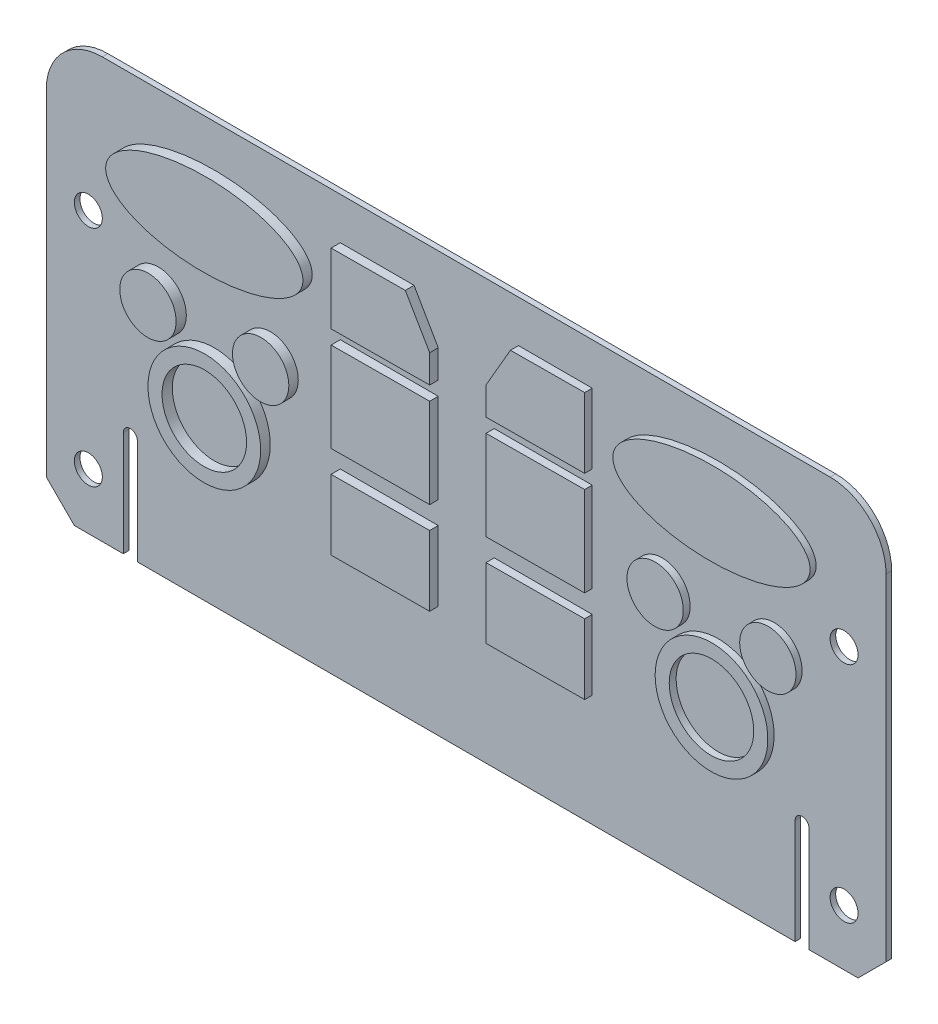
SolidWorks part; units mm, degrees
ref_plane "Front Plane" through (0, 0, 0) normal (0, 0, 1) x (1, 0, 0)
ref_plane "Top Plane" through (0, 0, 0) normal (0, 1, 0) x (1, 0, 0)
ref_plane "Right Plane" through (0, 0, 0) normal (1, 0, 0) x (0, 0, -1)
sketch "Sketch1" plane through (0, 0, 0) normal (0, 0, 1) x (1, 0, 0)
  line L1 (-300, 150) -> (0, 150)
  line L2 (-300, 150) -> (-300, 0)
  line L3 (-300, 0) -> (0, 0)
  line L4 (0, 150) -> (0, 0)
  line L5 (-300, 150) -> (0, 0) construction
  line L6 (-300, 0) -> (0, 150) construction
  point P0 (-150, 75)
  dimension "D1" = 300
  dimension "D2" = 150
extrude "PCB Base" add sketch "Sketch1" along normal blind 2
sketch "Sketch4" plane through (0, 0, 0) normal (0, 0, -1) x (-1, 0, 0)
  line L0 (140, 120) -> (131.3397, 135)
  line L1 (105, 40) -> (140, 40)
  line L2 (105, 40) -> (105, 65)
  line L3 (105, 65) -> (140, 65)
  line L4 (140, 40) -> (140, 65)
  line L5 (105, 40) -> (140, 65) construction
  line L6 (105, 65) -> (140, 40) construction
  line L7 (105, 73) -> (140, 73)
  line L8 (105, 73) -> (105, 105)
  line L9 (105, 105) -> (140, 105)
  line L10 (140, 73) -> (140, 105)
  line L11 (105, 73) -> (140, 105) construction
  line L12 (105, 105) -> (140, 73) construction
  line L13 (105, 110) -> (140, 110)
  line L14 (105, 110) -> (105, 135)
  line L15 (105, 135) -> (131.3397, 135)
  line L16 (140, 110) -> (140, 120)
  line L17 (105, 110) -> (133.8684, 130.6203) construction
  line L18 (105, 135) -> (140, 110) construction
  line L19 (150, 0) -> (150, 150) construction
  line L20 (300, 0) -> (0, 0) construction
  line L21 (0, 150) -> (300, 150) construction
  line L22 (195, 135) -> (160, 110) construction
  line L23 (195, 110) -> (166.1316, 130.6203) construction
  line L24 (195, 105) -> (160, 73) construction
  line L25 (195, 73) -> (160, 105) construction
  line L26 (195, 65) -> (160, 40) construction
  line L27 (195, 40) -> (160, 65) construction
  line L28 (160, 110) -> (160, 120)
  line L29 (195, 135) -> (168.6603, 135)
  line L30 (195, 110) -> (195, 135)
  line L31 (195, 110) -> (160, 110)
  line L32 (160, 73) -> (160, 105)
  line L33 (195, 105) -> (160, 105)
  line L34 (195, 73) -> (195, 105)
  line L35 (195, 73) -> (160, 73)
  line L36 (160, 40) -> (160, 65)
  line L37 (195, 65) -> (160, 65)
  line L38 (195, 40) -> (195, 65)
  line L39 (195, 40) -> (160, 40)
  line L40 (160, 120) -> (168.6603, 135)
  circle A0 centre (40, 85) radius 10
  circle A1 centre (80, 85) radius 10
  circle A2 centre (60, 60) radius 15
  circle A3 centre (60, 60) radius 20
  circle A4 centre (240, 60) radius 20
  circle A5 centre (240, 60) radius 15
  circle A6 centre (220, 85) radius 10
  circle A7 centre (260, 85) radius 10
  ellipse E0 centre (60, 120) end of major axis (95, 120) minor radius 15
  ellipse E1 centre (240, 120) end of major axis (205, 120) minor radius 15
  point P11 (122.5, 52.5)
  point P21 (122.5, 89)
  point P27 (122.5, 122.5)
  point P68 (177.5, 122.5)
  point P69 (177.5, 89)
  point P70 (177.5, 52.5)
  dimension "D1" = 20
  dimension "D5" = 30
  dimension "D8" = 5
  dimension "D2" = 40
  dimension "D3" = 85
  dimension "D4" = 40
  dimension "D6" = 60
  dimension "D7" = 60
  dimension "D9" = 30
  dimension "D10" = 70
  dimension "D11" = 120
  dimension "D12" = 105
  dimension "D13" = 40
  dimension "D14" = 73
  dimension "D15" = 110
  dimension "D16" = 25
  dimension "D17" = 32
  dimension "D18" = 35
  dimension "D19" = 120
  dimension "D20" = 30
extrude "Boss-Extrude3" add sketch "Sketch4" along normal blind 4
ref_plane "Plane1" through (0, 0, 0) normal (-0.0033, 0, -1) x (-1, 0, 0.0033)
mirror "Mirror1" about plane through (0, 0, 0) normal (-0.0033, 0, -1) of "Boss-Extrude3"
sketch "Sketch5" plane through (0, 0, 0) normal (0, 0, -1) x (-1, 0, 0)
  line L0 (300, 0) -> (0, 0) construction
  line L1 (27.5, 37.5) -> (32.5, 37.5)
  line L2 (27.5, 37.5) -> (27.5, 0)
  line L3 (27.5, 0) -> (32.5, 0)
  line L4 (32.5, 37.5) -> (32.5, 0)
  line L5 (27.5, 37.5) -> (32.5, 0) construction
  line L6 (27.5, 0) -> (32.5, 37.5) construction
  line L7 (10, 0) -> (0, 10)
  line L8 (0, 0) -> (0, 150) construction
  line L9 (150, 0) -> (150, 150) construction
  line L10 (0, 150) -> (300, 150) construction
  line L11 (272.5, 0) -> (267.5, 37.5) construction
  line L12 (272.5, 37.5) -> (267.5, 0) construction
  line L13 (290, 0) -> (300, 10)
  line L14 (267.5, 37.5) -> (267.5, 0)
  line L15 (272.5, 0) -> (267.5, 0)
  line L16 (272.5, 37.5) -> (272.5, 0)
  line L17 (272.5, 37.5) -> (267.5, 37.5)
  arc A0 (32.5, 37.5) -> (27.5, 37.5) centre (30, 37.5) ccw
  circle A1 centre (15, 20) radius 5
  circle A2 centre (15, 100) radius 5
  circle A3 centre (285, 100) radius 5
  circle A4 centre (285, 20) radius 5
  arc A5 (267.5, 37.5) -> (272.5, 37.5) centre (270, 37.5) cw
  point P0 (30, 18.75)
  point P9 (30, 40)
  point P35 (270, 18.75)
  line M23 (0, 150) -> (0, 0)
  line M24 (0, 0) -> (300, 0)
  line M25 (300, 0) -> (300, 150)
  dimension "D1" = 27.5
  dimension "D7" = 10
  dimension "D8" = 10
  dimension "D2" = 5
  dimension "D3" = 40
  dimension "D4" = 20
  dimension "D5" = 80
  dimension "D6" = 15
  dimension "D9" = 10
extrude "Cut-Extrude1" cut sketch "Sketch5" against normal up to next contours A2 | A1 | L7 M24 M23 | L4 L1 L2 M24 | L1 A0 | A3 | A4 | L13 M24 M25 | L16 L17 L14 M24 | A5 L17
fillet "Fillet1" radius 20 2 edges at (-300, 150, 1) (0, 150, 1)
sketch "Sketch6" plane through (0, 0, 0) normal (0, 0, -1) x (-1, 0, 0)
  line L0 (267.5, 0) -> (32.5, 0) construction
  line L1 (39, 0) -> (41, 0)
  line L2 (39, 0) -> (39, 25)
  line L3 (39, 25) -> (41, 25)
  line L4 (41, 0) -> (41, 25)
  line L5 (44, 0) -> (44, 25)
  line L6 (46, 0) -> (46, 25)
  line L7 (44, 25) -> (46, 25)
  line L8 (44, 0) -> (46, 0)
  line L9 (49, 0) -> (49, 25)
  line L10 (51, 0) -> (51, 25)
  line L11 (49, 25) -> (51, 25)
  line L12 (49, 0) -> (51, 0)
  line L13 (54, 0) -> (54, 25)
  line L14 (56, 0) -> (56, 25)
  line L15 (54, 25) -> (56, 25)
  line L16 (54, 0) -> (56, 0)
  line L17 (59, 0) -> (59, 25)
  line L18 (61, 0) -> (61, 25)
  line L19 (59, 25) -> (61, 25)
  line L20 (59, 0) -> (61, 0)
  line L21 (64, 0) -> (64, 25)
  line L22 (66, 0) -> (66, 25)
  line L23 (64, 25) -> (66, 25)
  line L24 (64, 0) -> (66, 0)
  line L25 (69, 0) -> (69, 25)
  line L26 (71, 0) -> (71, 25)
  line L27 (69, 25) -> (71, 25)
  line L28 (69, 0) -> (71, 0)
  line L29 (74, 0) -> (74, 25)
  line L30 (76, 0) -> (76, 25)
  line L31 (74, 25) -> (76, 25)
  line L32 (74, 0) -> (76, 0)
  line L33 (79, 0) -> (79, 25)
  line L34 (81, 0) -> (81, 25)
  line L35 (79, 25) -> (81, 25)
  line L36 (79, 0) -> (81, 0)
  line L37 (84, 0) -> (84, 25)
  line L38 (86, 0) -> (86, 25)
  line L39 (84, 25) -> (86, 25)
  line L40 (84, 0) -> (86, 0)
  line L41 (89, 0) -> (89, 25)
  line L42 (91, 0) -> (91, 25)
  line L43 (89, 25) -> (91, 25)
  line L44 (89, 0) -> (91, 0)
  line L45 (94, 0) -> (94, 25)
  line L46 (96, 0) -> (96, 25)
  line L47 (94, 25) -> (96, 25)
  line L48 (94, 0) -> (96, 0)
  line L49 (99, 0) -> (99, 25)
  line L50 (101, 0) -> (101, 25)
  line L51 (99, 25) -> (101, 25)
  line L52 (99, 0) -> (101, 0)
  line L53 (104, 0) -> (104, 25)
  line L54 (106, 0) -> (106, 25)
  line L55 (104, 25) -> (106, 25)
  line L56 (104, 0) -> (106, 0)
  line L57 (109, 0) -> (109, 25)
  line L58 (111, 0) -> (111, 25)
  line L59 (109, 25) -> (111, 25)
  line L60 (109, 0) -> (111, 0)
  line L61 (114, 0) -> (114, 25)
  line L62 (116, 0) -> (116, 25)
  line L63 (114, 25) -> (116, 25)
  line L64 (114, 0) -> (116, 0)
  line L65 (119, 0) -> (119, 25)
  line L66 (121, 0) -> (121, 25)
  line L67 (119, 25) -> (121, 25)
  line L68 (119, 0) -> (121, 0)
  line L69 (124, 0) -> (124, 25)
  line L70 (126, 0) -> (126, 25)
  line L71 (124, 25) -> (126, 25)
  line L72 (124, 0) -> (126, 0)
  line L73 (129, 0) -> (129, 25)
  line L74 (131, 0) -> (131, 25)
  line L75 (129, 25) -> (131, 25)
  line L76 (129, 0) -> (131, 0)
  line L77 (134, 0) -> (134, 25)
  line L78 (136, 0) -> (136, 25)
  line L79 (134, 25) -> (136, 25)
  line L80 (134, 0) -> (136, 0)
  line L81 (139, 0) -> (139, 25)
  line L82 (141, 0) -> (141, 25)
  line L83 (139, 25) -> (141, 25)
  line L84 (139, 0) -> (141, 0)
  line L85 (144, 0) -> (144, 25)
  line L86 (146, 0) -> (146, 25)
  line L87 (144, 25) -> (146, 25)
  line L88 (144, 0) -> (146, 0)
  line L89 (149, 0) -> (149, 25)
  line L90 (151, 0) -> (151, 25)
  line L91 (149, 25) -> (151, 25)
  line L92 (149, 0) -> (151, 0)
  line L93 (154, 0) -> (154, 25)
  line L94 (156, 0) -> (156, 25)
  line L95 (154, 25) -> (156, 25)
  line L96 (154, 0) -> (156, 0)
  line L97 (159, 0) -> (159, 25)
  line L98 (161, 0) -> (161, 25)
  line L99 (159, 25) -> (161, 25)
  line L100 (159, 0) -> (161, 0)
  line L101 (164, 0) -> (164, 25)
  line L102 (166, 0) -> (166, 25)
  line L103 (164, 25) -> (166, 25)
  line L104 (164, 0) -> (166, 0)
  line L105 (169, 0) -> (169, 25)
  line L106 (171, 0) -> (171, 25)
  line L107 (169, 25) -> (171, 25)
  line L108 (169, 0) -> (171, 0)
  line L109 (174, 0) -> (174, 25)
  line L110 (176, 0) -> (176, 25)
  line L111 (174, 25) -> (176, 25)
  line L112 (174, 0) -> (176, 0)
  line L113 (179, 0) -> (179, 25)
  line L114 (181, 0) -> (181, 25)
  line L115 (179, 25) -> (181, 25)
  line L116 (179, 0) -> (181, 0)
  line L117 (184, 0) -> (184, 25)
  line L118 (186, 0) -> (186, 25)
  line L119 (184, 25) -> (186, 25)
  line L120 (184, 0) -> (186, 0)
  line L121 (189, 0) -> (189, 25)
  line L122 (191, 0) -> (191, 25)
  line L123 (189, 25) -> (191, 25)
  line L124 (189, 0) -> (191, 0)
  line L125 (194, 0) -> (194, 25)
  line L126 (196, 0) -> (196, 25)
  line L127 (194, 25) -> (196, 25)
  line L128 (194, 0) -> (196, 0)
  line L129 (199, 0) -> (199, 25)
  line L130 (201, 0) -> (201, 25)
  line L131 (199, 25) -> (201, 25)
  line L132 (199, 0) -> (201, 0)
  line L133 (204, 0) -> (204, 25)
  line L134 (206, 0) -> (206, 25)
  line L135 (204, 25) -> (206, 25)
  line L136 (204, 0) -> (206, 0)
  line L137 (209, 0) -> (209, 25)
  line L138 (211, 0) -> (211, 25)
  line L139 (209, 25) -> (211, 25)
  line L140 (209, 0) -> (211, 0)
  line L141 (214, 0) -> (214, 25)
  line L142 (216, 0) -> (216, 25)
  line L143 (214, 25) -> (216, 25)
  line L144 (214, 0) -> (216, 0)
  line L145 (219, 0) -> (219, 25)
  line L146 (221, 0) -> (221, 25)
  line L147 (219, 25) -> (221, 25)
  line L148 (219, 0) -> (221, 0)
  line L149 (224, 0) -> (224, 25)
  line L150 (226, 0) -> (226, 25)
  line L151 (224, 25) -> (226, 25)
  line L152 (224, 0) -> (226, 0)
  line L153 (229, 0) -> (229, 25)
  line L154 (231, 0) -> (231, 25)
  line L155 (229, 25) -> (231, 25)
  line L156 (229, 0) -> (231, 0)
  line L157 (234, 0) -> (234, 25)
  line L158 (236, 0) -> (236, 25)
  line L159 (234, 25) -> (236, 25)
  line L160 (234, 0) -> (236, 0)
  line L161 (239, 0) -> (239, 25)
  line L162 (241, 0) -> (241, 25)
  line L163 (239, 25) -> (241, 25)
  line L164 (239, 0) -> (241, 0)
  line L165 (244, 0) -> (244, 25)
  line L166 (246, 0) -> (246, 25)
  line L167 (244, 25) -> (246, 25)
  line L168 (244, 0) -> (246, 0)
  line L169 (249, 0) -> (249, 25)
  line L170 (251, 0) -> (251, 25)
  line L171 (249, 25) -> (251, 25)
  line L172 (249, 0) -> (251, 0)
  line L173 (254, 0) -> (254, 25)
  line L174 (256, 0) -> (256, 25)
  line L175 (254, 25) -> (256, 25)
  line L176 (254, 0) -> (256, 0)
  line L177 (259, 0) -> (259, 25)
  line L178 (261, 0) -> (261, 25)
  line L179 (259, 25) -> (261, 25)
  line L180 (259, 0) -> (261, 0)
  point P6 (0, 0)
  dimension "D1" = 25
  dimension "D2" = 6.5
  dimension "D3" = 2
  dimension "D5" = 3
  dimension "D4" = 45
extrude "Cut-Extrude2" cut sketch "Sketch6" against normal blind 0.01
